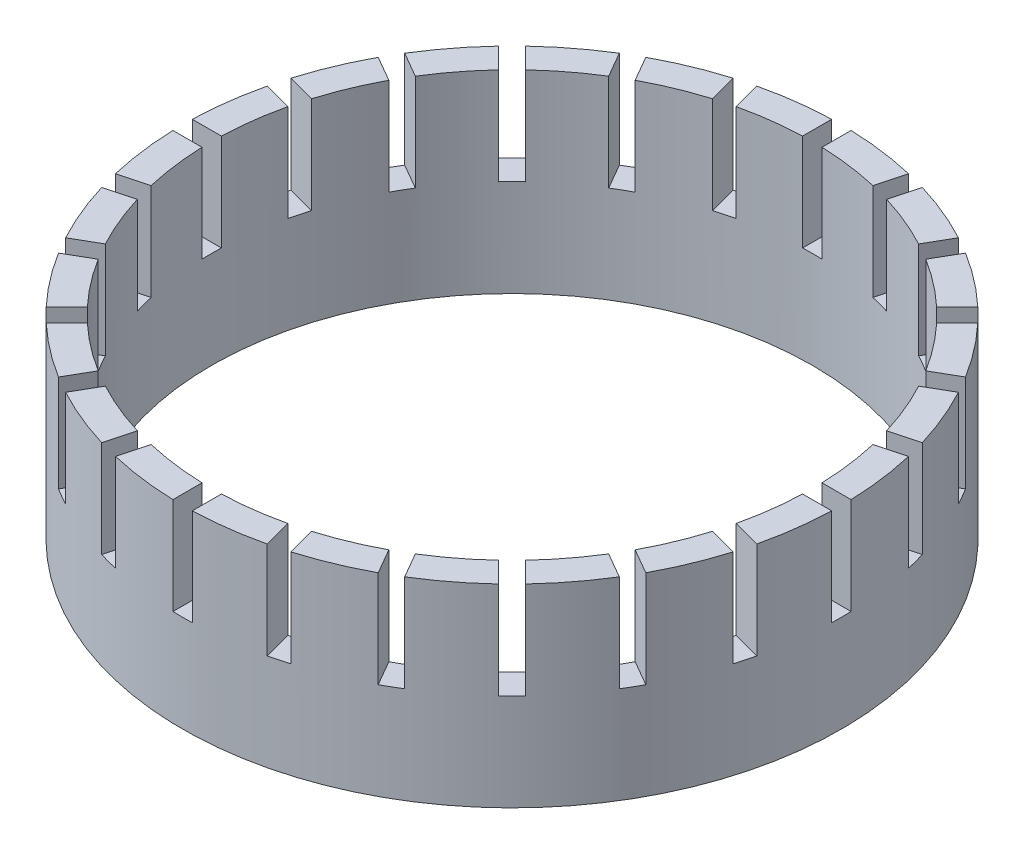
SolidWorks part; units mm, degrees
ref_plane "Front Plane" through (0, 0, 0) normal (0, 0, 1) x (1, 0, 0)
ref_plane "Top Plane" through (0, 0, 0) normal (0, 1, 0) x (1, 0, 0)
ref_plane "Right Plane" through (0, 0, 0) normal (1, 0, 0) x (0, 0, -1)
sketch "Sketch1" plane through (0, 0, 0) normal (0, 0, 1) x (1, 0, 0)
  line L0 (55, 0) -> (-55, 0) construction
  line L6 (-31, 0) -> (-34, 0)
  line L8 (-31, 0) -> (-31, 20)
  line L9 (-31, 20) -> (-34, 20)
  line L10 (-34, 0) -> (-34, 20)
  line L11 (0, -55) -> (0, 55) construction
  dimension "D1" = 31
  dimension "D2" = 3
  dimension "D3" = 20
ref_axis "Axis1" through (0, -1.9092, 0) along (0, 1, 0)
revolve "Revolve1" add sketch "Sketch1" angle 360 about axis through (0, -1.9092, 0) along (0, 1, 0)
sketch "Sketch2" plane through (0, 0, 0) normal (0, 0, 1) x (1, 0, 0)
  line L0 (0, -11) -> (0, 11) construction
  line L1 (-1, 48.7227) -> (1, 48.7227)
  line L2 (-1, 48.7227) -> (-1, 10)
  line L3 (-1, 10) -> (1, 10)
  line L4 (1, 48.7227) -> (1, 10)
  line L5 (-1, 48.7227) -> (1, 10) construction
  line L6 (-1, 10) -> (1, 48.7227) construction
  line L7 (37.4, 0) -> (-37.4, 0) construction
  point P0 (0, 29.3613)
  dimension "D1" = 2
  dimension "D2" = 10
extrude "Cut-Extrude1" cut sketch "Sketch2" against normal blind 40
pattern_circular "CirPattern1" count 24 every 15 about axis through (0, 0, 0) along (0, 1, 0) of "Cut-Extrude1"
